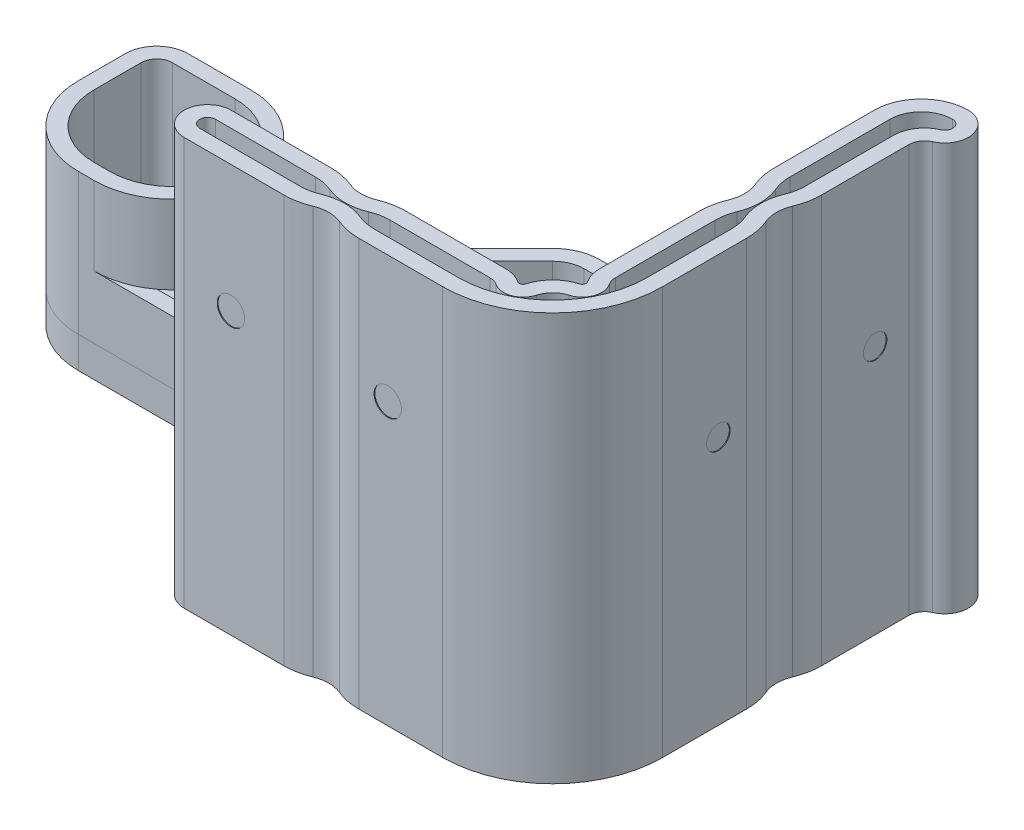
SolidWorks part; units mm, degrees
ref_plane "Front Plane" through (0, 0, 0) normal (0, 0, 1) x (1, 0, 0)
ref_plane "Top Plane" through (0, 0, 0) normal (0, 1, 0) x (1, 0, 0)
ref_plane "Right Plane" through (0, 0, 0) normal (1, 0, 0) x (0, 0, -1)
sketch "Sketch1" plane through (0, 0, 0) normal (0, 1, 0) x (1, 0, 0)
  line L1 (-21.5, 13.9196) -> (-21.5, 17.5) construction
  line L2 (-17.5, -21.5) -> (17.5, -21.5) construction
  line L3 (19.5, -3) -> (19.5, -9.2063)
  line L4 (19.5, 9.2063) -> (19.5, 3)
  line L5 (21.5, 21.5) -> (-21.5, -21.5) construction
  line L7 (-17.5, 21.5) -> (17.5, 21.5) construction
  line L8 (-11.4637, 10) -> (-11.4637, -10) construction
  line L9 (-11.4637, 10) -> (-11.4637, -10) construction
  line L10 (0, 0) -> (0, 15.6621) construction
  line L11 (0, 15.6621) -> (-15.6378, 15.6621) construction
  line L12 (-56.5, 10) -> (-37.6385, 10)
  line L13 (-50.5, -10) -> (-37.6385, -10)
  line L14 (-60.5, 0) -> (-60.5, 6)
  line L16 (-89.5, 10) -> (-37.6385, 10) construction
  line L17 (21.5, -17.5) -> (21.5, 17.5) construction
  line L19 (-47.2344, 5.9689) -> (-39.8131, 6)
  line L20 (-47.2344, -5.9689) -> (-39.8131, -6)
  line L21 (-21.5, -21.5) -> (21.5, 21.5) construction
  line L22 (18.5, 2) -> (17.5499, 2)
  line L24 (-17.5, 23.5) -> (17.5, 23.5)
  line L25 (23.5, -17.5) -> (23.5, 17.5)
  line L26 (-17.5, -23.5) -> (17.5, -23.5)
  line L27 (-89.5, -10) -> (-37.6385, -10) construction
  line L28 (-23.5, 10) -> (-23.5, 17.5) construction
  line L29 (-23.5, -17.5) -> (-23.5, -10) construction
  line L30 (18.5, -2) -> (17.5499, -2)
  line L31 (-3, -19.5) -> (-9.2063, -19.5)
  line L32 (9.2063, -19.5) -> (3, -19.5)
  line L33 (-23.4637, 0) -> (-16, 0) construction
  line L34 (2, -18.5) -> (2, -17.5499)
  line L35 (-2, -18.5) -> (-2, -17.5499)
  line L36 (-19.5, 3) -> (-19.5, 9.2063)
  line L37 (-19.5, -9.2063) -> (-19.5, -3)
  line L38 (-18.5, -2) -> (-17.5499, -2)
  line L39 (-9.2063, 19.5) -> (-3, 19.5)
  line L40 (-17.5, 19.5) -> (17.5, 19.5) construction
  line L41 (2, 18.5) -> (2, 17.5499)
  line L42 (-2, 18.5) -> (-2, 17.5499)
  line L43 (3, 19.5) -> (9.2063, 19.5)
  line L44 (0, 23.4637) -> (0, 16) construction
  line L45 (-18.5, 2) -> (-17.5499, 2)
  line L46 (-21.74, 21.7453) -> (-30.5718, 12.9245)
  line L47 (-21.74, -21.7453) -> (-30.5718, -12.9245)
  line L48 (-23.5, -3) -> (-23.5, -11.9221)
  line L49 (23.4637, 0) -> (16, 0) construction
  line L50 (-27.5, 0) -> (-21.5, 0) construction
  line L51 (-20.3267, -20.3302) -> (-29.1585, -11.5094) construction
  line L52 (-20.3267, -20.3302) -> (-20.3284, -20.3284)
  line L53 (-20.3267, 20.3302) -> (-29.1585, 11.5094) construction
  line L54 (0, -23.4637) -> (0, -16) construction
  line L55 (-26.0299, -2) -> (-24.5, -2)
  line L56 (-25.2067, -12.6296) -> (-30.1701, -7.6724)
  line L57 (-25.2067, 12.6296) -> (-30.1701, 7.6724)
  line L58 (-60.5, 0) -> (-50.5, 0) construction
  line L59 (-26.0299, 2) -> (-24.5, 2)
  line L61 (-18.9133, -18.9151) -> (-18.9142, -18.9142)
  line L62 (-18.9133, -18.9151) -> (-27.7452, -10.0943) construction
  line L64 (-23.5, 3) -> (-23.5, 11.9221)
  line L65 (-21.5, -17.5) -> (-21.5, -10) construction
  line L66 (-89.5, 8) -> (-37.6385, 8) construction
  line L67 (-89.5, -8) -> (-37.6385, -8) construction
  line L69 (-21.5, 10) -> (-21.5, 17.5) construction
  arc A0 (-60.5, 6) -> (-56.5, 10) centre (-56.5, 6) cw
  arc A1 (-23.5, -17.5) -> (-17.5, -23.5) centre (-17.5, -17.5) ccw construction
  circle A2 centre (-33.5, 0) radius 2 construction
  arc A3 (-17.5, 21.5) -> (-21.5, 17.5) centre (-17.5, 17.5) ccw construction
  arc A4 (-21.5, -17.5) -> (-17.5, -21.5) centre (-17.5, -17.5) ccw construction
  arc A6 (-48.014, -4.3478) -> (-48.014, 4.3478) centre (-53.5, 0) ccw
  arc A8 (-39.0252, 4.3789) -> (-39.0252, -4.3789) centre (-33.5, 0) ccw
  arc A9 (-17.5, 23.5) -> (-23.5, 17.5) centre (-17.5, 17.5) ccw construction
  circle A10 centre (0, 0) radius 12
  circle A11 centre (-15.6378, 15.6621) radius 2
  circle A12 centre (15.6621, 15.6378) radius 2
  arc A14 (21.5, -17.5) -> (17.5, -21.5) centre (17.5, -17.5) cw construction
  arc A15 (17.5, 21.5) -> (21.5, 17.5) centre (17.5, 17.5) cw construction
  arc A17 (17.5, 23.5) -> (23.5, 17.5) centre (17.5, 17.5) cw
  arc A18 (23.5, -17.5) -> (17.5, -23.5) centre (17.5, -17.5) cw
  circle A20 centre (15.6378, -15.6621) radius 2
  circle A21 centre (-15.6621, -15.6378) radius 2
  circle A22 centre (-53.5, 0) radius 2 construction
  circle A23 centre (-53.5, 0) radius 7 construction
  circle A25 centre (-33.5, 0) radius 7.05 construction
  arc A26 (-26.9579, 2.6273) -> (-29.9649, 6.0996) centre (-33.5, 0) ccw
  arc A27 (-17.5, 23.5) -> (-21.74, 21.7453) centre (-17.5, 17.5) ccw
  arc A28 (-30.1701, 7.6724) -> (-29.9649, 6.0996) centre (-29.4635, 6.9648) ccw
  arc A29 (-26.0299, 2) -> (-26.9579, 2.6273) centre (-26.0299, 3) cw
  arc A32 (13.7831, -8.1256) -> (15.5999, -3.5556) centre (0, 0) ccw
  arc A33 (13.7831, -8.1256) -> (14.7756, -9.6248) centre (14.6446, -8.6335) ccw
  arc A34 (18.0864, -10.1167) -> (14.7756, -9.6248) centre (15.5724, -15.6501) ccw
  arc A35 (17.5499, -2) -> (15.5999, -3.5556) centre (17.5499, -4) ccw
  arc A36 (18.0864, -10.1167) -> (19.5, -9.2063) centre (18.5, -9.2063) ccw
  arc A37 (19.5, -3) -> (18.5, -2) centre (18.5, -3) ccw
  arc A38 (18.0864, 10.1167) -> (14.7756, 9.6248) centre (15.5724, 15.6501) cw
  arc A39 (17.5499, 2) -> (15.5999, 3.5556) centre (17.5499, 4) cw
  arc A40 (13.7831, 8.1256) -> (14.7756, 9.6248) centre (14.6446, 8.6335) cw
  arc A41 (13.7831, 8.1256) -> (15.5999, 3.5556) centre (0, 0) cw
  arc A42 (18.5, 2) -> (19.5, 3) centre (18.5, 3) ccw
  arc A43 (18.0864, 10.1167) -> (19.5, 9.2063) centre (18.5, 9.2063) cw
  arc A44 (-8.1256, -13.7831) -> (-3.5556, -15.5999) centre (0, 0) ccw
  arc A45 (-10.1167, 18.0864) -> (-9.6248, 14.7756) centre (-15.6501, 15.5724) cw
  arc A46 (8.1256, 13.7831) -> (3.5556, 15.5999) centre (0, 0) ccw
  arc A47 (-8.1256, -13.7831) -> (-9.6248, -14.7756) centre (-8.6335, -14.6446) ccw
  arc A48 (8.1256, 13.7831) -> (9.6248, 14.7756) centre (8.6335, 14.6446) ccw
  arc A49 (10.1167, 18.0864) -> (9.6248, 14.7756) centre (15.6501, 15.5724) ccw
  arc A50 (2, 17.5499) -> (3.5556, 15.5999) centre (4, 17.5499) ccw
  arc A51 (-2, 17.5499) -> (-3.5556, 15.5999) centre (-4, 17.5499) cw
  arc A52 (-10.1167, -18.0864) -> (-9.6248, -14.7756) centre (-15.6501, -15.5724) ccw
  arc A53 (-8.1256, 13.7831) -> (-9.6248, 14.7756) centre (-8.6335, 14.6446) cw
  arc A54 (-2, -17.5499) -> (-3.5556, -15.5999) centre (-4, -17.5499) ccw
  arc A55 (-8.1256, 13.7831) -> (-3.5556, 15.5999) centre (0, 0) cw
  arc A56 (-10.1167, -18.0864) -> (-9.2063, -19.5) centre (-9.2063, -18.5) ccw
  arc A57 (-3, -19.5) -> (-2, -18.5) centre (-3, -18.5) ccw
  arc A58 (10.1167, -18.0864) -> (9.6248, -14.7756) centre (15.6501, -15.5724) cw
  arc A59 (2, -17.5499) -> (3.5556, -15.5999) centre (4, -17.5499) cw
  arc A60 (8.1256, -13.7831) -> (9.6248, -14.7756) centre (8.6335, -14.6446) cw
  arc A61 (8.1256, -13.7831) -> (3.5556, -15.5999) centre (0, 0) cw
  arc A62 (2, -18.5) -> (3, -19.5) centre (3, -18.5) ccw
  arc A63 (10.1167, -18.0864) -> (9.2063, -19.5) centre (9.2063, -18.5) cw
  arc A64 (-13.7831, 8.1256) -> (-15.5999, 3.5556) centre (0, 0) ccw
  arc A65 (-13.7831, 8.1256) -> (-14.7756, 9.6248) centre (-14.6446, 8.6335) ccw
  arc A66 (-18.0864, 10.1167) -> (-14.7756, 9.6248) centre (-15.5724, 15.6501) ccw
  arc A67 (-17.5499, 2) -> (-15.5999, 3.5556) centre (-17.5499, 4) ccw
  arc A68 (-18.0864, 10.1167) -> (-19.5, 9.2063) centre (-18.5, 9.2063) ccw
  arc A69 (-19.5, 3) -> (-18.5, 2) centre (-18.5, 3) ccw
  arc A70 (-18.0864, -10.1167) -> (-14.7756, -9.6248) centre (-15.5724, -15.6501) cw
  arc A71 (-17.5499, -2) -> (-15.5999, -3.5556) centre (-17.5499, -4) cw
  arc A72 (-13.7831, -8.1256) -> (-14.7756, -9.6248) centre (-14.6446, -8.6335) cw
  arc A73 (10.1167, 18.0864) -> (9.2063, 19.5) centre (9.2063, 18.5) ccw
  arc A74 (-13.7831, -8.1256) -> (-15.5999, -3.5556) centre (0, 0) cw
  arc A75 (-18.5, -2) -> (-19.5, -3) centre (-18.5, -3) ccw
  arc A76 (3, 19.5) -> (2, 18.5) centre (3, 18.5) ccw
  arc A77 (-18.0864, -10.1167) -> (-19.5, -9.2063) centre (-18.5, -9.2063) cw
  arc A78 (-2, 18.5) -> (-3, 19.5) centre (-3, 18.5) ccw
  arc A79 (-21.74, -21.7453) -> (-17.5, -23.5) centre (-17.5, -17.5) ccw
  arc A80 (-10.1167, 18.0864) -> (-9.2063, 19.5) centre (-9.2063, 18.5) cw
  arc A81 (-17.5, 23.5) -> (-23.5, 17.5) centre (-17.5, 17.5) ccw construction
  arc A82 (-23.5, -17.5) -> (-17.5, -23.5) centre (-17.5, -17.5) ccw construction
  arc A83 (-37.6385, -10) -> (-30.5718, -12.9245) centre (-37.6385, -20) cw
  arc A84 (-37.6385, 10) -> (-30.5718, 12.9245) centre (-37.6385, 20) ccw
  arc A88 (-47.2344, 5.9689) -> (-48.014, 4.3478) centre (-47.2303, 4.9689) ccw
  arc A89 (-47.2344, -5.9689) -> (-48.014, -4.3478) centre (-47.2303, -4.9689) cw
  arc A90 (-89.5, 8) -> (-89.5, -8) centre (-89.5, 0) ccw construction
  arc A91 (-37.6385, 8) -> (-29.1585, 11.5094) centre (-37.6385, 20) ccw construction
  arc A92 (-37.6385, -8) -> (-29.1585, -11.5094) centre (-37.6385, -20) cw construction
  arc A93 (-17.5, 21.5) -> (-20.3267, 20.3302) centre (-17.5, 17.5) ccw construction
  arc A94 (-20.3267, -20.3302) -> (-17.5, -21.5) centre (-17.5, -17.5) ccw construction
  arc A95 (-24.5, 2) -> (-23.5, 3) centre (-24.5, 3) ccw
  arc A96 (-23.5, 11.9221) -> (-25.2067, 12.6296) centre (-24.5, 11.9221) ccw
  arc A97 (-39.8131, -6) -> (-39.0252, -4.3789) centre (-39.8089, -5) ccw
  arc A98 (-39.8131, 6) -> (-39.0252, 4.3789) centre (-39.8089, 5) cw
  arc A99 (-23.5, -11.9221) -> (-25.2067, -12.6296) centre (-24.5, -11.9221) cw
  circle A100 centre (-53.5, 0) radius 3
  arc A101 (-24.5, -2) -> (-23.5, -3) centre (-24.5, -3) cw
  arc A102 (-26.0299, -2) -> (-26.9579, -2.6273) centre (-26.0299, -3) ccw
  arc A103 (-89.5, 10) -> (-89.5, -10) centre (-89.5, 0) ccw construction
  arc A104 (-30.1701, -7.6724) -> (-29.9649, -6.0996) centre (-29.4635, -6.9648) cw
  arc A105 (-26.9579, -2.6273) -> (-29.9649, -6.0996) centre (-33.5, 0) cw
  arc A106 (-60.5, 0) -> (-50.5, -10) centre (-50.5, 0) ccw
  circle A110 centre (-33.5, 0) radius 3.05
  point P0 (0.0699, 0.0699)
  point P5 (0, 0)
  point P33 (-53.5, 6)
  point P43 (-53.5, -6)
  point P51 (0, 0)
  point P119 (-11.2855, 11.3418)
  point P207 (0, 0)
  point P227 (0, 0)
  point P238 (-26.7396, 2)
  point P244 (-21.5, -16.3317)
  point P251 (-57.1754, 5.9574)
  point P264 (-34.8226, -5.8524)
  point P265 (-48.516, -6)
  point P283 (-26.7396, -2)
  point P289 (-25.9608, -2)
  dimension "D3" = 4
  dimension "D4" = 4
  dimension "D5" = 2
  dimension "D9" = 1
  dimension "D14" = 4
  dimension "D7" = 10
  dimension "D2" = 2
  dimension "D6" = 2
  dimension "D8" = 2
  dimension "D10" = 4
  dimension "D16" = 4
  dimension "D17" = 4
extrude "Boss-Extrude1" add sketch "Sketch1" along normal blind 4
sketch "Sketch4" plane through (0, 4, 0) normal (0, 1, 0) x (1, 0, 0)
  line L8 (-60.5, 6) -> (-60.5, 0)
  line L9 (-60.5, 6) -> (-60.5, 0)
  line L14 (-37.6385, 10) -> (-56.5, 10)
  line L15 (-50.5, -10) -> (-37.6385, -10)
  line L16 (-30.5718, -12.9245) -> (-21.74, -21.7453)
  line L17 (-17.5, -23.5) -> (17.5, -23.5)
  line L18 (23.5, -17.5) -> (23.5, 17.5)
  line L19 (17.5, 23.5) -> (-17.5, 23.5)
  line L20 (-21.74, 21.7453) -> (-30.5718, 12.9245)
  line L21 (-37.6385, 10) -> (-56.5, 10)
  line L22 (-50.5, -10) -> (-37.6385, -10)
  line L23 (-30.5718, -12.9245) -> (-21.74, -21.7453)
  line L25 (-17.5, -23.5) -> (17.5, -23.5)
  line L26 (23.5, -17.5) -> (23.5, 17.5)
  line L27 (17.5, 23.5) -> (-17.5, 23.5)
  line L28 (-21.74, 21.7453) -> (-30.5718, 12.9245)
  arc A8 (-56.5, 10) -> (-60.5, 6) centre (-56.5, 6) ccw
  arc A9 (-56.5, 10) -> (-60.5, 6) centre (-56.5, 6) ccw
  arc A14 (-37.6385, 10) -> (-30.5718, 12.9245) centre (-37.6385, 20) ccw
  arc A15 (-60.5, 0) -> (-50.5, -10) centre (-50.5, 0) ccw
  arc A16 (-30.5718, -12.9245) -> (-37.6385, -10) centre (-37.6385, -20) ccw
  arc A17 (-21.74, -21.7453) -> (-17.5, -23.5) centre (-17.5, -17.5) ccw
  arc A18 (17.5, -23.5) -> (23.5, -17.5) centre (17.5, -17.5) ccw
  arc A19 (23.5, 17.5) -> (17.5, 23.5) centre (17.5, 17.5) ccw
  arc A20 (-17.5, 23.5) -> (-21.74, 21.7453) centre (-17.5, 17.5) ccw
  arc A21 (-37.6385, 10) -> (-30.5718, 12.9245) centre (-37.6385, 20) ccw
  arc A22 (-60.5, 0) -> (-50.5, -10) centre (-50.5, 0) ccw
  arc A23 (-30.5718, -12.9245) -> (-37.6385, -10) centre (-37.6385, -20) ccw
  arc A24 (-21.74, -21.7453) -> (-17.5, -23.5) centre (-17.5, -17.5) ccw
  arc A25 (17.5, -23.5) -> (23.5, -17.5) centre (17.5, -17.5) ccw
  arc A26 (23.5, 17.5) -> (17.5, 23.5) centre (17.5, 17.5) ccw
  arc A27 (-17.5, 23.5) -> (-21.74, 21.7453) centre (-17.5, 17.5) ccw
  dimension "D1" = 0
extrude "Extrude-Thin1" add sketch "Sketch4" along normal blind 8 separate body thin thin type one direction reverse wall 2
sketch "Sketch5" plane through (0, 4, 0) normal (0, 1, 0) x (1, 0, 0)
  line L0 (-20.3267, 20.3302) -> (-29.1585, 11.5094) construction
  line L1 (-26.22, 14.4442) -> (-29.1585, 11.5094) construction
  line L2 (-26.22, 14.3029) -> (-29.0878, 11.4387)
  line L3 (-21.1, -12.1803) -> (-21.1, 12.1803)
  line L4 (-21.5, 13.9196) -> (-21.5, 17.5) construction
  line L5 (-21.5, -14.3342) -> (-21.5, 14.3342) construction
  line L6 (-32.3993, 9.2041) -> (-36.9054, 7.0173) construction
  line L7 (-32.3993, -9.2041) -> (-36.9054, -7.0173) construction
  line L8 (-29.1585, -11.5094) -> (-26.22, -14.4442) construction
  line L9 (-21.1, -14.3342) -> (-21.1, 14.3342) construction
  line L10 (-32.3557, 9.1141) -> (-36.8618, 6.9274)
  line L11 (-32.3557, -9.1141) -> (-36.8618, -6.9274)
  line L12 (-29.0878, -11.4387) -> (-26.22, -14.3029)
  line L13 (-29.0878, -11.4387) -> (-26.1493, -14.3735) construction
  line L14 (-26.1493, 14.3735) -> (-29.0878, 11.4387) construction
  arc A0 (-32.3557, 9.1141) -> (-29.0878, 11.4387) centre (-37.6385, 20) ccw
  arc A1 (-36.9054, 7.0173) -> (-36.9054, -7.0173) centre (-33.5, 0) ccw construction
  arc A2 (-36.8618, 6.9274) -> (-36.8618, -6.9274) centre (-33.5, 0) ccw
  arc A3 (-29.0878, -11.4387) -> (-32.3557, -9.1141) centre (-37.6385, -20) ccw
  arc A4 (-26.22, -14.3029) -> (-21.1, -12.1803) centre (-24.1, -12.1803) ccw
  arc A5 (-26.22, 14.3029) -> (-21.1, 12.1803) centre (-24.1, 12.1803) cw
  arc A6 (-29.1585, -11.5094) -> (-37.6385, -8) centre (-37.6385, -20) ccw construction
  arc A7 (-37.6385, 8) -> (-29.1585, 11.5094) centre (-37.6385, 20) ccw construction
  arc A8 (-29.1585, -11.5094) -> (-32.3993, -9.2041) centre (-37.6385, -20) ccw construction
  arc A9 (-32.3993, 9.2041) -> (-29.1585, 11.5094) centre (-37.6385, 20) ccw construction
  dimension "D1" = 0.4
  dimension "D2" = 0.1
  dimension "D3" = 3
extrude "Extrude-Thin2" add sketch "Sketch5" along normal blind 8 separate body thin thin type one direction reverse wall 2
sketch "Sketch6" plane through (0, 0, 0) normal (0, 1, 0) x (1, 0, 0)
  line L0 (-33.5, 0) -> (-23.5, 0) construction
  line L1 (-56.5, 10) -> (-37.6385, 10) construction
  line L2 (-23.5, -10) -> (-43.5, -10)
  line L3 (-23.5, -10) -> (-23.5, 10)
  line L4 (-23.5, 10) -> (-63.5, 10)
  line L7 (-63.5, 10) -> (-103.5, 10)
  line L9 (-43.5, -10) -> (-103.5, -10)
  line L10 (-103.5, 10) -> (-103.5, -10)
sketch "Sketch7" plane through (0, 12, 0) normal (0, 1, 0) x (1, 0, 0)
  line L0 (-60.5, 0) -> (-60.5, 6)
  line L2 (-56.5, 10) -> (-48.5, 10)
  line L3 (-56.5, 10) -> (-37.6385, 10) construction
  line L4 (-50.5, -10) -> (-37.6385, -10) construction
  line L5 (-48.5, -10) -> (-50.5, -10)
  arc A0 (-60.5, 0) -> (-50.5, -10) centre (-50.5, 0) ccw construction
  arc A1 (-60.5, 0) -> (-50.5, -10) centre (-50.5, 0) ccw
  arc A2 (-48.5, 10) -> (-48.5, -10) centre (-48.4621, 0) cw
  arc A3 (-56.5, 10) -> (-60.5, 6) centre (-56.5, 6) ccw construction
  arc A4 (-56.5, 10) -> (-60.5, 6) centre (-56.5, 6) ccw
extrude "Extrude-Thin3" add sketch "Sketch7" along normal blind 10 thin
sketch "Sketch8" plane through (0, 0, 0) normal (0, 1, 0) x (1, 0, 0)
  line L0 (-17.5, -23.5) -> (-4.77, -23.5)
  line L1 (-17.5, -29.5) -> (-4.77, -29.5)
  line L2 (-17.5, -25.5) -> (17.5, -25.5) construction
  line L3 (-17.5, -27.5) -> (17.5, -27.5) construction
  line L4 (0, -25.5) -> (0, -26.45) construction
  line L5 (0, -27.5) -> (0, -26.55) construction
  line L6 (0, -26.45) -> (0, -23.5) construction
  line L7 (0, -26.55) -> (0, -29.5) construction
  line L8 (0, -26.45) -> (0, -24.45) construction
  line L9 (4.77, -23.5) -> (17.5, -23.5)
  line L10 (4.77, -29.5) -> (15.4706, -29.5)
  line L11 (-3.4265, -25.5) -> (-3.4265, -27.5) construction
  line L12 (-3.4265, -26.5) -> (-4.6197, -26.5) construction
  line L13 (29.5, -4.77) -> (29.5, -15.4706)
  line L15 (21.7426, -21.7426) -> (28.8137, -28.8137) construction
  line L16 (26.5, 3.4265) -> (26.5, 4.6197) construction
  line L17 (25.5, 3.4265) -> (27.5, 3.4265) construction
  line L18 (26.45, 0) -> (24.45, 0) construction
  line L19 (26.55, 0) -> (29.5, 0) construction
  line L20 (26.45, 0) -> (23.5, 0) construction
  line L21 (27.5, 0) -> (26.55, 0) construction
  line L22 (25.5, 0) -> (26.45, 0) construction
  line L23 (27.5, 17.5) -> (27.5, -17.5) construction
  line L24 (25.5, 17.5) -> (25.5, -17.5) construction
  line L26 (23.5, -4.77) -> (23.5, -17.5)
  line L27 (29.5, 15.9174) -> (29.5, 4.77)
  line L28 (23.5, 17.5) -> (23.5, 4.77)
  arc A0 (-17.5, -23.5) -> (-17.5, -29.5) centre (-17.5, -26.5) ccw
  arc A1 (15.4706, -29.5) -> (29.5, -15.4706) centre (15.4706, -15.4706) ccw
  arc A2 (17.5, -25.5) -> (17.5, -27.5) centre (17.5, -26.5) cw construction
  arc A3 (-17.5, -25.5) -> (-17.5, -27.5) centre (-17.5, -26.5) ccw construction
  arc A4 (-1.7049, -24.1104) -> (1.7049, -24.1104) centre (0, -20) ccw
  arc A5 (1.7049, -24.1104) -> (4.77, -23.5) centre (4.77, -31.5) cw
  arc A6 (-1.7049, -24.1104) -> (-4.77, -23.5) centre (-4.77, -31.5) ccw
  arc A7 (1.7049, -28.8896) -> (4.77, -29.5) centre (4.77, -21.5) ccw
  arc A8 (-1.7049, -28.8896) -> (1.7049, -28.8896) centre (0, -33) cw
  arc A9 (-1.7049, -28.8896) -> (-4.77, -29.5) centre (-4.77, -21.5) cw
  arc A10 (24.1703, -19.7165) -> (23.8926, -20.474) centre (23.7541, -19.9936) cw
  arc A11 (25.5, 17.5) -> (27.5, 17.5) centre (26.5, 17.5) cw construction
  arc A12 (25.5, -17.5) -> (27.5, -17.5) centre (26.5, -17.5) ccw construction
  arc A13 (28.8896, 1.7049) -> (29.5, 4.77) centre (21.5, 4.77) ccw
  arc A14 (28.8896, 1.7049) -> (28.8896, -1.7049) centre (33, 0) ccw
  arc A15 (28.8896, -1.7049) -> (29.5, -4.77) centre (21.5, -4.77) cw
  arc A16 (24.1104, 1.7049) -> (23.5, 4.77) centre (31.5, 4.77) cw
  arc A17 (24.1104, -1.7049) -> (23.5, -4.77) centre (31.5, -4.77) ccw
  arc A18 (24.1104, 1.7049) -> (24.1104, -1.7049) centre (20, 0) cw
  arc A19 (23.5, 17.5) -> (29.5, 23.5) centre (29.5, 17.5) cw
  arc A20 (23.8926, -20.474) -> (20.474, -23.8926) centre (25.2782, -25.2782) ccw
  arc A21 (17.5, -23.5) -> (19.7165, -24.1703) centre (17.5, -27.5) cw
  arc A22 (23.5, -17.5) -> (24.1703, -19.7165) centre (27.5, -17.5) ccw
  arc A23 (29.5, 23.5) -> (30.7, 17.7505) centre (29.5, 20.5) cw
  arc A24 (20.474, -23.8926) -> (19.7165, -24.1703) centre (19.9936, -23.7541) cw
  arc A25 (30.7, 17.7505) -> (29.5, 15.9174) centre (31.5, 15.9174) ccw
  point P28 (2.7482, -23.5)
  point P82 (23.5, -2.7482)
  dimension "D2" = 2
  dimension "D1" = 0.5
extrude "Extrude-Thin4" add sketch "Sketch8" along normal blind 52 separate body thin
sketch "Sketch9" plane through (0, 0, 29.5) normal (0, 0, 1) x (1, 0, 0)
  circle A0 centre (8.4706, 35.8209) radius 1.75
  circle A1 centre (-1.5294, 35.8209) radius 1.75
  circle A2 centre (-11.5294, 35.8209) radius 1.75
extrude "Cut-Extrude1" cut sketch "Sketch9" against normal blind 0.1
sketch "Sketch10" plane through (29.5, 0, 0) normal (1, 0, 0) x (0, 0, -1)
  circle A0 centre (-8.3721, 31.8367) radius 1.5
  circle A1 centre (1.6279, 31.8367) radius 1.5
  circle A2 centre (11.6279, 31.8367) radius 1.5
extrude "Cut-Extrude2" cut sketch "Sketch10" against normal blind 0.1
